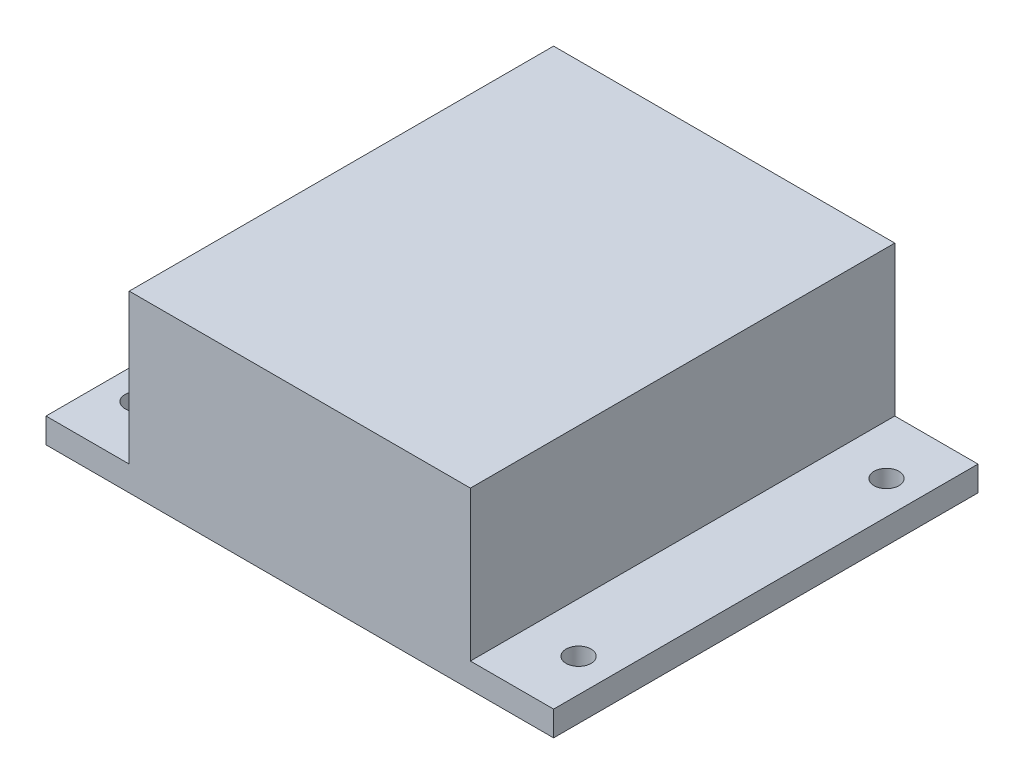
SolidWorks part; units mm, degrees
ref_plane "Plano frontal" through (0, 0, 0) normal (0, 0, 1) x (1, 0, 0)
ref_plane "Plano superior" through (0, 0, 0) normal (0, 1, 0) x (1, 0, 0)
ref_plane "Plano direito" through (0, 0, 0) normal (1, 0, 0) x (0, 0, -1)
sketch "Esboço1" plane through (0, 0, 0) normal (0, 1, 0) x (1, 0, 0)
  line L1 (30.5, -25.5) -> (-30.5, -25.5)
  line L2 (30.5, -25.5) -> (30.5, 25.5)
  line L3 (30.5, 25.5) -> (-30.5, 25.5)
  line L4 (-30.5, -25.5) -> (-30.5, 25.5)
  line L5 (30.5, -25.5) -> (-30.5, 25.5) construction
  line L6 (30.5, 25.5) -> (-30.5, -25.5) construction
  line L7 (26.5, -18.5) -> (-26.5, -18.5) construction
  line L8 (26.5, -18.5) -> (26.5, 18.5) construction
  line L9 (26.5, 18.5) -> (-26.5, 18.5) construction
  line L10 (-26.5, -18.5) -> (-26.5, 18.5) construction
  line L11 (26.5, -18.5) -> (-26.5, 18.5) construction
  line L12 (26.5, 18.5) -> (-26.5, -18.5) construction
  circle A0 centre (-26.5, 18.5) radius 1.5
  circle A1 centre (-26.5, -18.5) radius 1.5
  circle A2 centre (26.5, -18.5) radius 1.5
  circle A3 centre (26.5, 18.5) radius 1.5
  point P0 (0, 0)
  point P6 (0, 0)
  dimension "D3" = 3
  dimension "D1" = 61
  dimension "D2" = 51
  dimension "D4" = 53
  dimension "D6" = 37
extrude "Ressalto-extrusão1" add sketch "Esboço1" along normal blind 21
sketch "Esboço2" plane through (0, 21, 0) normal (0, 1, 0) x (1, 0, 0)
  line L0 (-30.5, -25.5) -> (30.5, -25.5) construction
  line L1 (-30.5, 25.5) -> (-20.5, 25.5)
  line L2 (-30.5, 25.5) -> (-30.5, -25.5)
  line L3 (-30.5, -25.5) -> (-20.5, -25.5)
  line L4 (-20.5, 25.5) -> (-20.5, -25.5)
  line L5 (30.5, 25.5) -> (-30.5, 25.5) construction
  line L6 (30.5, -25.5) -> (20.5, -25.5)
  line L7 (30.5, -25.5) -> (30.5, 25.5)
  line L8 (30.5, 25.5) -> (20.5, 25.5)
  line L9 (20.5, -25.5) -> (20.5, 25.5)
  dimension "D1" = 10
extrude "Corte-extrusão1" cut sketch "Esboço2" against normal offset from surface (18 mm away) 3 up to face at (0, 0, 0)
